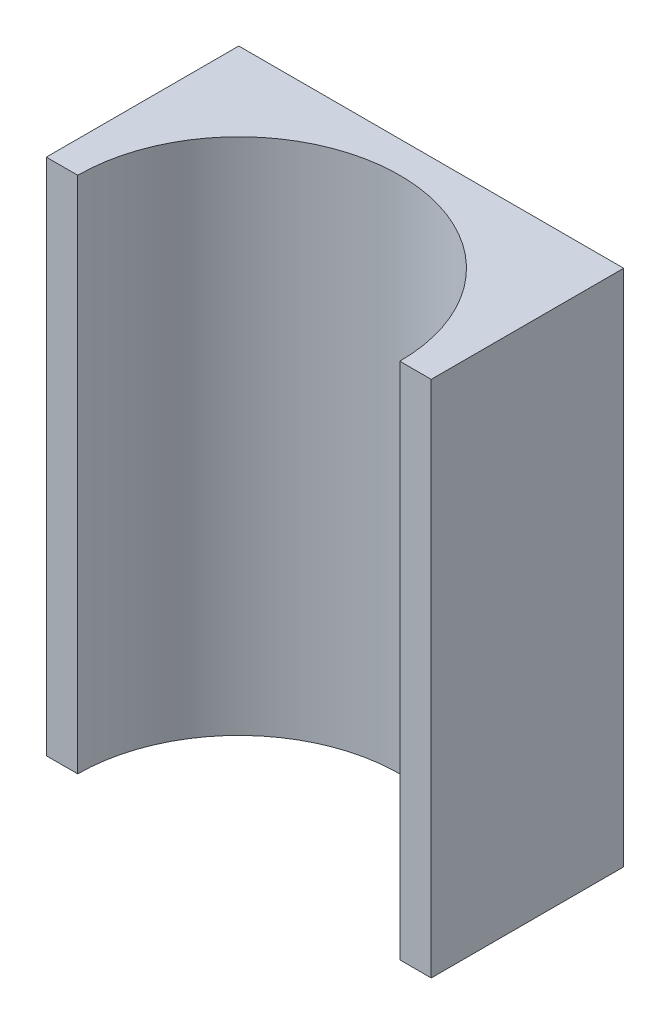
SolidWorks part; units mm, degrees
ref_plane "Front Plane" through (0, 0, 0) normal (0, 0, 1) x (1, 0, 0)
ref_plane "Top Plane" through (0, 0, 0) normal (0, 1, 0) x (1, 0, 0)
ref_plane "Right Plane" through (0, 0, 0) normal (1, 0, 0) x (0, 0, -1)
sketch "Sketch1" plane through (0, 0, 0) normal (0, 1, 0) x (1, 0, 0)
  line L0 (41, -24.5) -> (49, -24.5)
  line L1 (-49, 24.5) -> (49, 24.5)
  line L2 (-49, 24.5) -> (-49, -24.5)
  line L3 (-49, -24.5) -> (-41, -24.5)
  line L4 (49, 24.5) -> (49, -24.5)
  line L5 (-49, 24.5) -> (49, -24.5) construction
  line L6 (-49, -24.5) -> (49, 24.5) construction
  arc A0 (41, -24.5) -> (-41, -24.5) centre (0, -24.5) ccw
  point P0 (0, 0)
  point P10 (-41, -24.5)
  point P11 (41, -24.5)
  point P12 (0, -24.5)
  dimension "D1" = 49
  dimension "D2" = 98
extrude "Boss-Extrude1" add sketch "Sketch1" along normal blind 132
